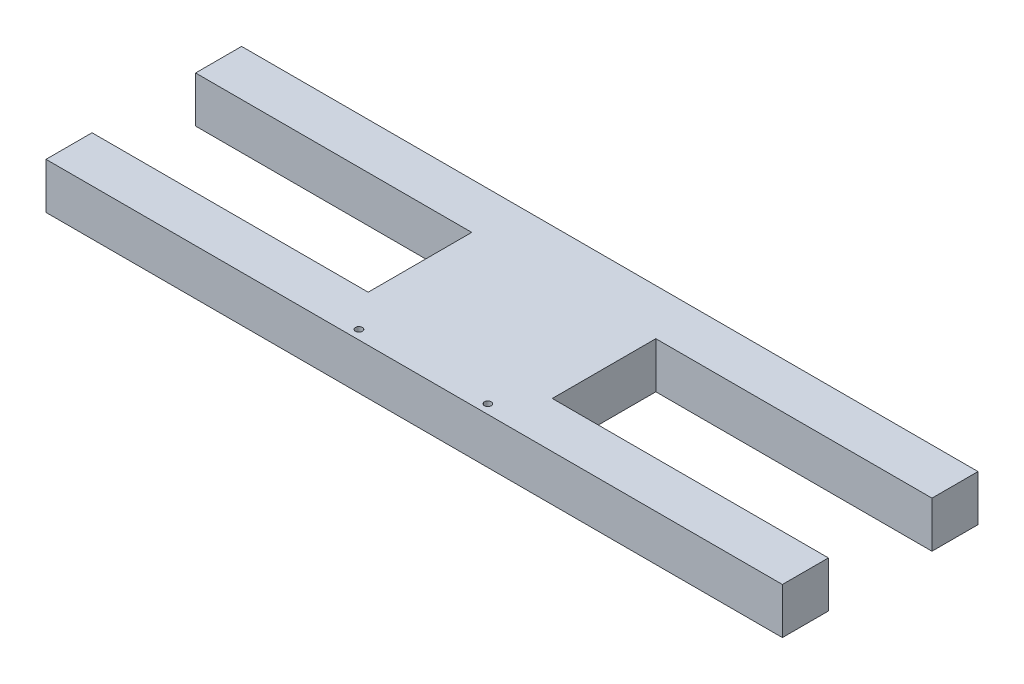
SolidWorks part; units mm, degrees
ref_plane "Front Plane" through (0, 0, 0) normal (0, 0, 1) x (1, 0, 0)
ref_plane "Top Plane" through (0, 0, 0) normal (0, 1, 0) x (1, 0, 0)
ref_plane "Right Plane" through (0, 0, 0) normal (1, 0, 0) x (0, 0, -1)
sketch "Sketch1" plane through (0, 0, 0) normal (0, 1, 0) x (1, 0, 0)
  line L1 (-160, 42.5) -> (160, 42.5)
  line L2 (-160, 42.5) -> (-160, -42.5)
  line L3 (-160, -42.5) -> (160, -42.5)
  line L4 (160, 42.5) -> (160, -42.5)
  line L5 (-160, 42.5) -> (160, -42.5) construction
  line L6 (-160, -42.5) -> (160, 42.5) construction
  line L7 (-40, 22.5) -> (40, 22.5)
  line L8 (-40, 22.5) -> (-40, -22.5)
  line L9 (-40, -22.5) -> (40, -22.5)
  line L10 (40, 22.5) -> (40, -22.5)
  line L11 (-40, 22.5) -> (40, -22.5) construction
  line L12 (-40, -22.5) -> (40, 22.5) construction
  line L13 (-40, 22.5) -> (-160, 22.5)
  line L14 (-40, 22.5) -> (-40, -22.5)
  line L15 (-40, -22.5) -> (-160, -22.5)
  line L16 (-160, 22.5) -> (-160, -22.5)
  line L17 (40, -22.5) -> (160, -22.5)
  line L18 (40, -22.5) -> (40, 22.5)
  line L19 (40, 22.5) -> (160, 22.5)
  line L20 (160, -22.5) -> (160, 22.5)
  point P0 (0, 0)
  point P6 (0, 0)
  dimension "D1" = 85
  dimension "D2" = 320
  dimension "D3" = 80
  dimension "D4" = 20
extrude "Boss-Extrude2" add sketch "Sketch1" along normal blind 20 contours L17 L9 L15 L2 L3 L4 | L10 L7 L8 L9 | L7 L19 L4 L1 L2 L13
sketch "Sketch3" plane through (0, 20, 0) normal (0, 1, 0) x (1, 0, 0)
  line L1 (-40, -22.5) -> (40, -22.5)
  line L2 (-40, -22.5) -> (-40, -38.5)
  line L3 (-40, -38.5) -> (40, -38.5)
  line L4 (40, -22.5) -> (40, -38.5)
  circle A0 centre (-28, -38.5) radius 1.5
  circle A1 centre (28, -38.5) radius 1.5
  dimension "D1" = 3
  dimension "D2" = 3
  dimension "1" = 16
  dimension "D3" = 12
  dimension "D4" = 12
extrude "Cut-Extrude7" cut sketch "Sketch3" against normal blind 20 contours A0 | A1
